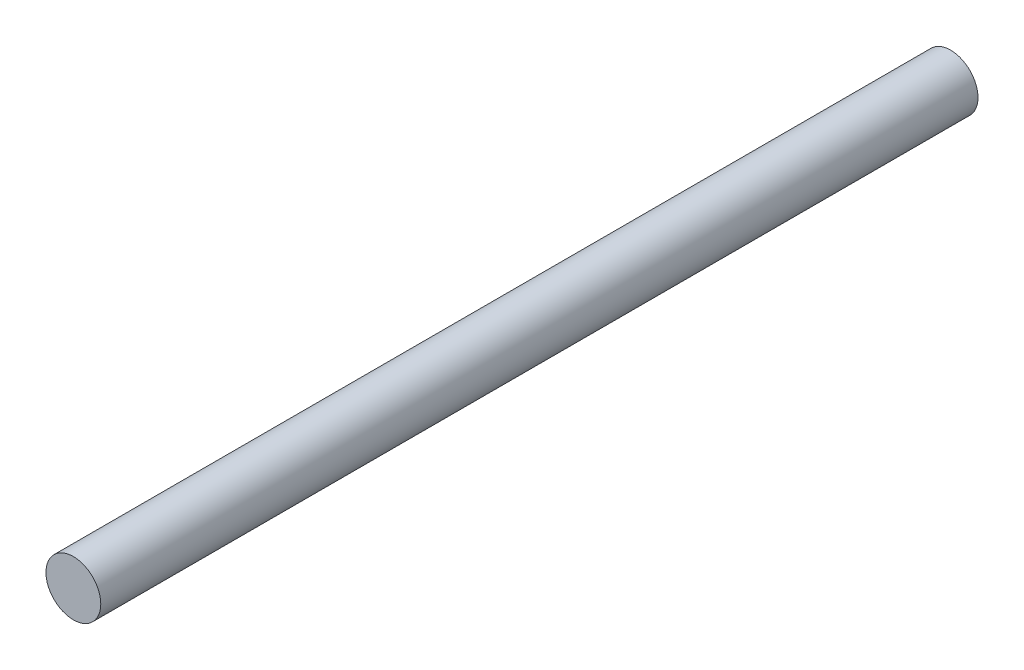
SolidWorks part; units mm, degrees
ref_plane "Front Plane" through (0, 0, 0) normal (0, 0, 1) x (1, 0, 0)
ref_plane "Top Plane" through (0, 0, 0) normal (0, 1, 0) x (1, 0, 0)
ref_plane "Right Plane" through (0, 0, 0) normal (1, 0, 0) x (0, 0, -1)
sketch "Sketch1" plane through (0, 0, 0) normal (0, 0, 1) x (1, 0, 0)
  circle A0 centre (0, 0) radius 3
extrude "Boss-Extrude1" add sketch "Sketch1" along normal blind 96
